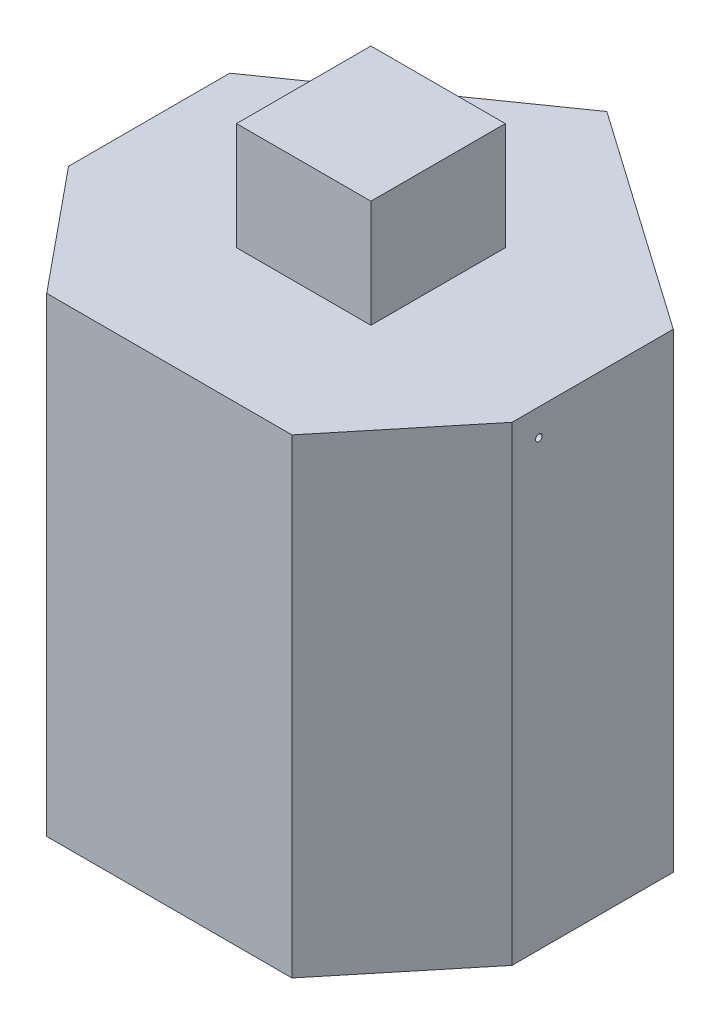
SolidWorks part; units mm, degrees
ref_plane "Front" through (0, 0, 0) normal (0, 0, 1) x (1, 0, 0)
ref_plane "Top" through (0, 0, 0) normal (0, 1, 0) x (1, 0, 0)
ref_plane "Right" through (0, 0, 0) normal (1, 0, 0) x (0, 0, -1)
sketch "Esquisse1" plane through (0, 0, 0) normal (0, 1, 0) x (1, 0, 0)
  line L0 (-165, 60) -> (0, 175.5705)
  line L1 (-165, -60) -> (165, -60) construction
  line L2 (-165, -60) -> (-165, 60)
  line L3 (-165, 60) -> (165, 60) construction
  line L4 (165, -60) -> (165, 60)
  line L5 (-165, -60) -> (165, 60) construction
  line L6 (-165, 60) -> (165, -60) construction
  line L7 (0, 175.5705) -> (165, 60)
  line L8 (-165, -60) -> (-91.2414, -150)
  line L9 (-91.2414, -150) -> (91.2414, -150)
  line L10 (91.2414, -150) -> (165, -60)
  circle A0 centre (0, 0) radius 175.5705 construction
  point P0 (0, 0)
  dimension "D1" = 330
  dimension "D2" = 120
  dimension "D3" = 150
extrude "Boss.-Extru.1" add sketch "Esquisse1" along normal blind 350
sketch "Esquisse2" plane through (0, 0, 0) normal (0, 1, 0) x (1, 0, 0)
  line L1 (-50, -50) -> (50, -50)
  line L2 (-50, -50) -> (-50, 50)
  line L3 (-50, 50) -> (50, 50)
  line L4 (50, -50) -> (50, 50)
  line L5 (-50, -50) -> (50, 50) construction
  line L6 (-50, 50) -> (50, -50) construction
  point P0 (0, 0)
  dimension "D1" = 100
extrude "Boss.-Extru.2" add sketch "Esquisse2" along normal blind 430
sketch "Esquisse3" plane through (165, 0, 0) normal (1, 0, 0) x (0, 0, -1)
  line L0 (175.5705, 350) -> (175.5705, 0) construction
  line L1 (175.5705, 0) -> (120, 0)
  line L2 (175.5705, 0) -> (175.5705, 340)
  line L3 (175.5705, 340) -> (65, 340)
  line L4 (120, 0) -> (120, 280)
  line L5 (60, 350) -> (175.5705, 350) construction
  line L10 (120, 280) -> (65, 280)
  line L11 (65, 340) -> (65, 280)
  line L12 (60, 0) -> (175.5705, 0) construction
  dimension "D1" = 10
  dimension "D3" = 120
  dimension "D4" = 60
  dimension "D5" = 65
extrude "Enlèv. mat.-Extru.1" cut sketch "Esquisse3" against normal through all
sketch "Esquisse4" plane through (165, 0, 0) normal (1, 0, 0) x (0, 0, -1)
  line L0 (50, 350) -> (-50, 350) construction
  circle A0 centre (-40, 330) radius 2.5
  dimension "D1" = 20
  dimension "D2" = 40
  dimension "D3" = 5
extrude "Enlèv. mat.-Extru.2" cut sketch "Esquisse4" against normal through all
